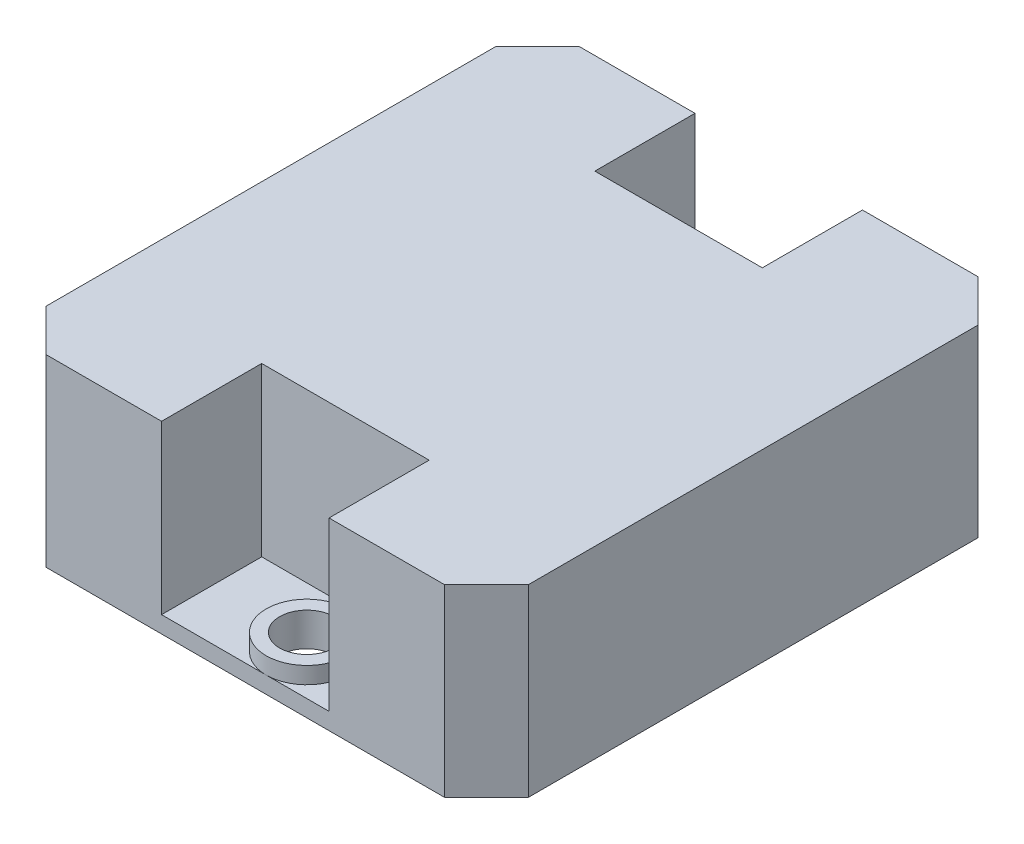
SolidWorks part; units mm, degrees
ref_plane "前视基准面" through (0, 0, 0) normal (0, 0, 1) x (1, 0, 0)
ref_plane "上视基准面" through (0, 0, 0) normal (0, 1, 0) x (1, 0, 0)
ref_plane "右视基准面" through (0, 0, 0) normal (1, 0, 0) x (0, 0, -1)
sketch "草图1" plane through (0, 0, 0) normal (0, 1, 0) x (1, 0, 0)
  line L0 (-28.8, 26.85) -> (-23.8, 31.85)
  line L1 (-23.8, 31.85) -> (23.8, 31.85)
  line L2 (-28.8, 26.85) -> (-28.8, -26.85)
  line L3 (-23.8, -31.85) -> (23.8, -31.85)
  line L4 (28.8, 26.85) -> (28.8, -26.85)
  line L5 (-28.8, 31.85) -> (28.8, -31.85) construction
  line L6 (-28.8, -31.85) -> (28.8, 31.85) construction
  line L7 (23.8, 31.85) -> (28.8, 26.85)
  line L8 (23.8, -31.85) -> (28.8, -26.85)
  line L9 (-28.8, -26.85) -> (-23.8, -31.85)
  line L10 (-28.8, 31.85) -> (2.5, 31.85) construction
  line L11 (2.5, 31.85) -> (2.5, 30.25) construction
  line L12 (2.5, 30.25) -> (2.5, 27) construction
  line L14 (0, 0) -> (59.303, 0) construction
  circle A0 centre (2.5, 27) radius 3.25
  circle A1 centre (2.5, -27) radius 3.25
  point P0 (0, 0)
  point P24 (28.8, 24.6553)
  dimension "D1" = 26.3
  dimension "D2" = 26.3
extrude "凸台-拉伸1" add sketch "草图1" along normal blind 22
sketch "草图2" plane through (0, 22, 0) normal (0, 1, 0) x (1, 0, 0)
  line L0 (0, 0) -> (0, -36.0697) construction
  line L1 (0, -31.8707) -> (0, -19.8707) construction
  line L2 (0, -31.8707) -> (0, -25.8707) construction
  line L3 (-23.8, -31.85) -> (23.8, -31.85) construction
  line L4 (-10, -19.8915) -> (10, -19.8915)
  line L5 (-10, -19.8915) -> (-10, -31.85)
  line L7 (10, -19.8915) -> (10, -31.85)
  line L8 (-10, -19.8915) -> (10, -31.85) construction
  line L9 (-10, -31.85) -> (10, -19.8915) construction
  line L10 (0, 0) -> (41.937, 0) construction
  line L11 (-10, 19.8915) -> (-10, 31.85)
  line L13 (10, 19.8915) -> (10, 31.85)
  line L14 (-10, 19.8915) -> (10, 19.8915)
  line L15 (-10, 31.85) -> (-10, 34.2473)
  line L16 (-10, 34.2473) -> (10, 34.2473)
  line L17 (10, 34.2473) -> (10, 31.85)
  line L18 (-10, -31.85) -> (-10, -34.3084)
  line L19 (-10, -34.3084) -> (10, -34.3084)
  line L20 (10, -34.3084) -> (10, -31.85)
  circle A0 centre (2.5, 27) radius 4.85
  circle A1 centre (2.5, -27) radius 4.85
extrude "切除-拉伸3" cut sketch "草图2" against normal blind 20
sketch "草图3" plane through (0, 22, 0) normal (0, 1, 0) x (1, 0, 0)
  circle A0 centre (2.5, 27) radius 6
  circle A1 centre (2.5, -27) radius 6
extrude "切除-拉伸4" cut sketch "草图3" against normal blind 18
